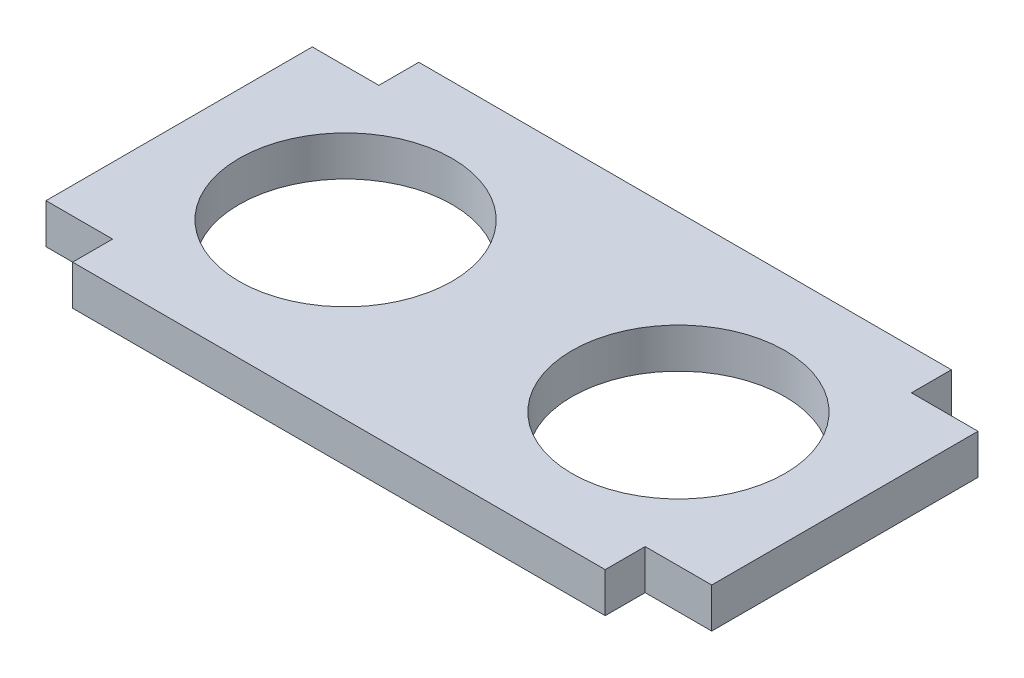
SolidWorks part; units mm, degrees
ref_plane "前视基准面" through (0, 0, 0) normal (0, 0, 1) x (1, 0, 0)
ref_plane "上视基准面" through (0, 0, 0) normal (0, 1, 0) x (1, 0, 0)
ref_plane "右视基准面" through (0, 0, 0) normal (1, 0, 0) x (0, 0, -1)
other "Configuration Table"
sketch "草图1" plane through (0, 0, 0) normal (0, 1, 0) x (1, 0, 0)
  line L0 (-20, 10) -> (-20, 13)
  line L1 (-25, -10) -> (-20, -10)
  line L2 (-25, -10) -> (-25, 10)
  line L3 (-25, 10) -> (-20, 10)
  line L4 (25, -10) -> (25, 10)
  line L7 (-20, -13) -> (20, -13)
  line L8 (-20, -13) -> (-20, -10)
  line L9 (-20, 13) -> (20, 13)
  line L10 (20, -13) -> (20, -10)
  line L12 (20, -10) -> (25, -10)
  line L15 (20, 10) -> (25, 10)
  line L16 (20, 10) -> (20, 13)
  point P0 (0, 0)
  point P6 (0, 0)
  dimension "D1" = 20
  dimension "D2" = 50
  dimension "D3" = 40
  dimension "D4" = 26
extrude "凸台-拉伸1" add sketch "草图1" along normal blind 3
sketch "草图2" plane through (0, 3, 0) normal (0, 1, 0) x (1, 0, 0)
  line L0 (0, 0) -> (0, -50000) construction
  circle A0 centre (12.5, 0) radius 8
  circle A1 centre (-12.5, 0) radius 8
  dimension "D1" = 16
  dimension "D2" = 12.5
extrude "切除-拉伸1" cut sketch "草图2" against normal blind 3
